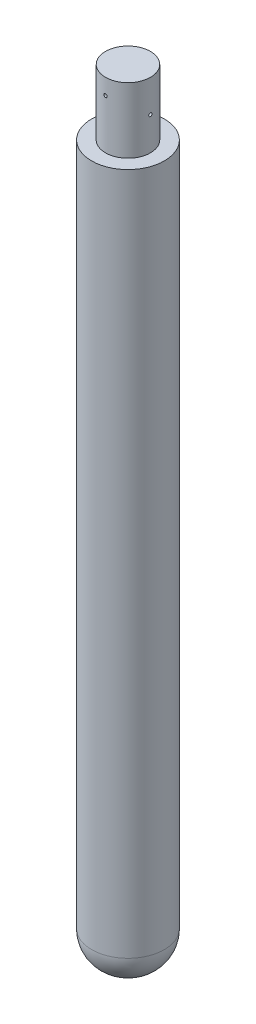
SolidWorks part; units mm, degrees
ref_plane "Front Plane" through (0, 0, 0) normal (0, 0, 1) x (1, 0, 0)
ref_plane "Top Plane" through (0, 0, 0) normal (0, 1, 0) x (1, 0, 0)
ref_plane "Right Plane" through (0, 0, 0) normal (1, 0, 0) x (0, 0, -1)
sketch "Sketch1" plane through (0, 0, 0) normal (0, 1, 0) x (1, 0, 0)
  circle A0 centre (0, 0) radius 11
extrude "Boss-Extrude1" add sketch "Sketch1" along normal blind 216.6667 contours A0
sketch "Sketch2" plane through (0, 0, 0) normal (0, 1, 0) x (1, 0, 0)
  circle A0 centre (0, 0) radius 6.8
extrude "Boss-Extrude2" add sketch "Sketch2" along normal blind 19.8 from offset 216.6667
fillet "Fillet1" radius 10 1 edges at (0, 0, 11)
sketch "Sketch3" plane through (0, 0, 0) normal (0, 0, 1) x (1, 0, 0)
  circle A0 centre (0, 231.6667) radius 0.5
extrude "Cut-Extrude1" cut sketch "Sketch3" against normal blind 9 from offset 1.44 offset against normal yes
mirror "Mirror1" about plane through (0, 0, 0) normal (0, 0, 1) of "Cut-Extrude1"
sketch "Sketch4" plane through (0, 0, 0) normal (1, 0, 0) x (0, 0, -1)
  line L2 (0, 12.1) -> (0, -12.1) construction
  circle A0 centre (0, 226.6667) radius 0.5
extrude "Cut-Extrude2" cut sketch "Sketch4" against normal blind 9 from offset 1.4 offset against normal yes
mirror "Mirror2" about plane through (0, 0, 0) normal (1, 0, 0) of "Cut-Extrude2"
equation "\"V\"=0"
